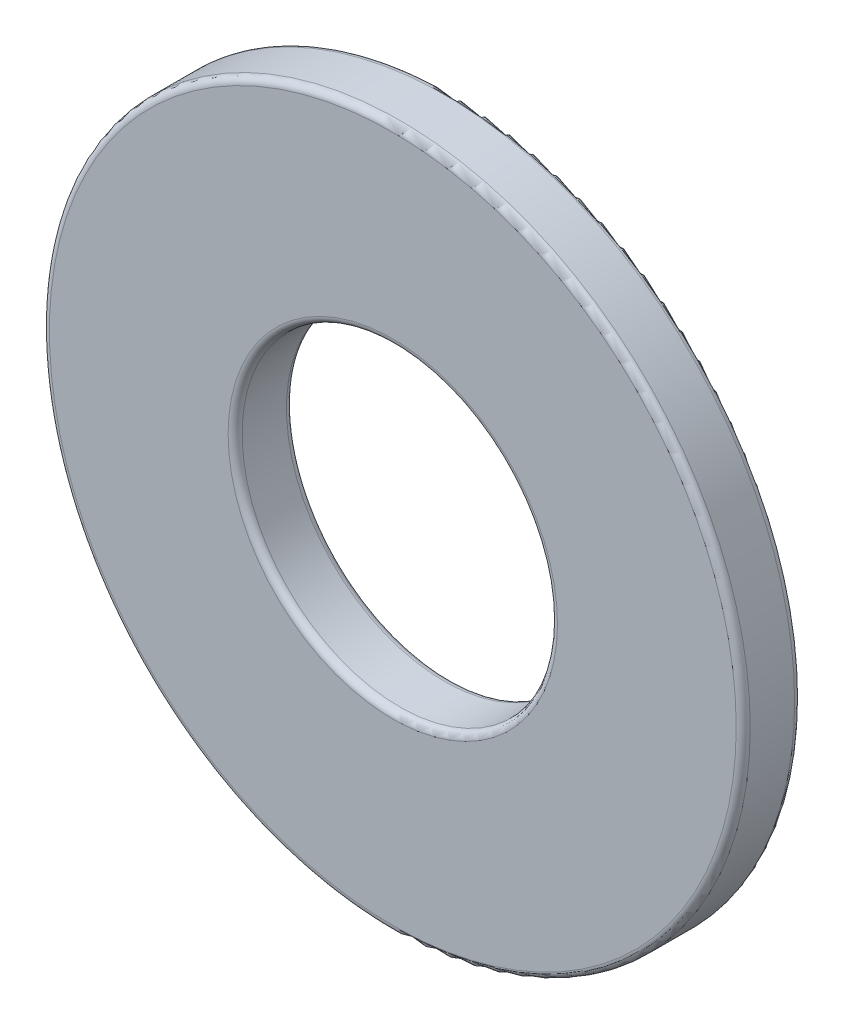
SolidWorks part; units mm, degrees
material "AISI 304"
ref_plane "Front Plane" through (0, 0, 0) normal (0, 0, 1) x (1, 0, 0)
ref_plane "Top Plane" through (0, 0, 0) normal (0, 1, 0) x (1, 0, 0)
ref_plane "Right Plane" through (0, 0, 0) normal (1, 0, 0) x (0, 0, -1)
sketch "Sketch1" plane through (0, 0, 0) normal (0, 0, 1) x (1, 0, 0)
  line L0 (0, 0) -> (1.35, 0) construction
  line L1 (0, -0.165) -> (0, 0.165) construction
  circle A0 centre (0, 0) radius 3
  circle A1 centre (0, 0) radius 1.35
  dimension "D1" = 90
  dimension "OD" = 6
  dimension "ID" = 2.7
sketch "Sketch2" plane through (0, 0, 0) normal (1, 0, 0) x (0, 0, -1)
  line L0 (-0.25, 3) -> (0.25, 3) construction
  point P5 (0, 3)
  dimension "Thickness" = 0.5
sketch "Sketch3" plane through (0, 0, 0) normal (0, 0, 1) x (1, 0, 0)
  circle A0 centre (0, 0) radius 1.35 construction
  circle A1 centre (0, 0) radius 3 construction
  circle A2 centre (0, 0) radius 1.35
  circle A3 centre (0, 0) radius 3
extrude "Boss-Extrude1" add sketch "Sketch3" against normal up to vertex (0.25 mm away) from vertex at 0.25 starting at point (0, 3, 0.25)
fillet "Fillet1" radius 0.06 4 edges at (3, 0, 0.25) (1.35, 0, 0.25) (3, 0, -0.25) (1.35, 0, -0.25)
